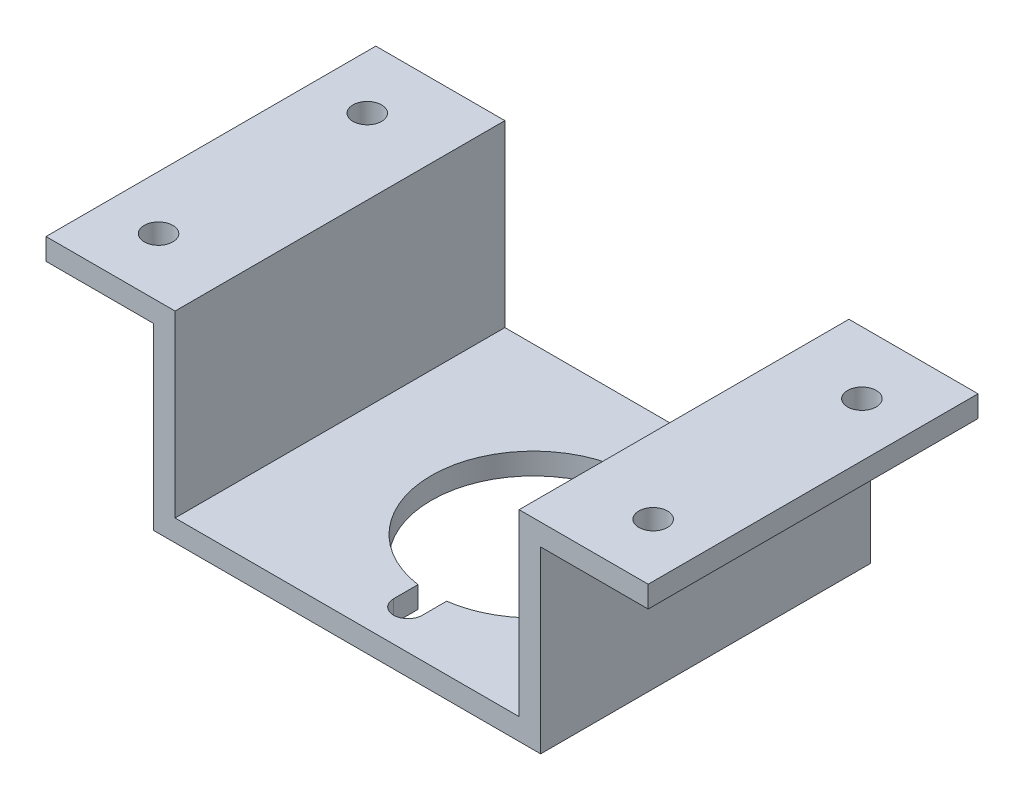
SolidWorks part; units mm, degrees
ref_plane "Front Plane" through (0, 0, 0) normal (0, 0, 1) x (1, 0, 0)
ref_plane "Top Plane" through (0, 0, 0) normal (0, 1, 0) x (1, 0, 0)
ref_plane "Right Plane" through (0, 0, 0) normal (1, 0, 0) x (0, 0, -1)
sketch "Sketch1" plane through (0, 0, 0) normal (0, 1, 0) x (1, 0, 0)
  line L1 (-23.0791, 14.3848) -> (26.9209, 14.3848)
  line L2 (-23.0791, 14.3848) -> (-23.0791, -25.6152)
  line L3 (-23.0791, -25.6152) -> (26.9209, -25.6152)
  line L4 (26.9209, 14.3848) -> (26.9209, -25.6152)
  dimension "D1" = 50
  dimension "D2" = 40
extrude "Boss-Extrude1" add sketch "Sketch1" along normal blind 3
sketch "Sketch2" plane through (0, 3, 0) normal (0, 1, 0) x (1, 0, 0)
  line L0 (-19.0791, 14.3848) -> (-19.0791, -25.6152)
  line L1 (26.9209, 14.3848) -> (-23.0791, 14.3848) construction
  line L2 (-23.0791, -25.6152) -> (26.9209, -25.6152) construction
  line L7 (-23.0791, 14.3848) -> (-23.0791, -25.6152)
  line L8 (-23.0791, -25.6152) -> (26.9209, -25.6152)
  line L9 (26.9209, -25.6152) -> (26.9209, 14.3848)
  line L10 (26.9209, 14.3848) -> (-23.0791, 14.3848)
  line L11 (-23.0791, 14.3848) -> (-23.0791, -25.6152)
  line L12 (-23.0791, -25.6152) -> (-19.0791, -25.6152)
  line L14 (-19.0791, 14.3848) -> (-23.0791, 14.3848)
  dimension "D1" = 0
  dimension "D2" = 4
sketch "Sketch5" plane through (0, 3, 0) normal (0, 1, 0) x (1, 0, 0)
  line L0 (24.9209, 14.3848) -> (24.9209, -25.6152)
  line L1 (26.9209, 14.3848) -> (-23.0791, 14.3848) construction
  line L2 (-23.0791, -25.6152) -> (26.9209, -25.6152) construction
  line L7 (-23.0791, 14.3848) -> (-23.0791, -25.6152)
  line L8 (-23.0791, -25.6152) -> (26.9209, -25.6152)
  line L9 (26.9209, -25.6152) -> (26.9209, 14.3848)
  line L10 (26.9209, 14.3848) -> (-23.0791, 14.3848)
  line L12 (24.9209, -25.6152) -> (26.9209, -25.6152)
  line L13 (26.9209, -25.6152) -> (26.9209, 14.3848)
  line L14 (26.9209, 14.3848) -> (24.9209, 14.3848)
  line L15 (-23.0791, 14.3848) -> (-23.0791, -25.6152)
  dimension "D1" = 0
  dimension "D2" = 2
sketch "Sketch6" plane through (0, 0, 0) normal (0, -1, 0) x (1, 0, 0)
  line L0 (-23.0791, 5.6152) -> (-1.0791, 5.6152)
  line L1 (-23.0791, -14.3848) -> (-23.0791, 25.6152) construction
  line L2 (6.9209, 5.6152) -> (6.9209, -11.8848)
  line L3 (-1.0791, 5.6152) -> (6.9209, 5.6152)
  line L4 (6.9209, 5.6152) -> (6.9209, 23.1152)
  line L5 (24.4209, 13.0152) -> (18.923, 13.0152)
  line L6 (6.9209, 5.6152) -> (24.4209, 5.6152)
  line L7 (24.4209, 5.6152) -> (24.4209, 13.0152)
  line L8 (24.4209, 5.6152) -> (24.4209, -1.7848)
  line L9 (24.4209, -1.7848) -> (18.923, -1.7848)
  arc A1 (18.923, 13.0152) -> (18.923, -1.7848) centre (6.9209, 5.6152) ccw
  circle A2 centre (6.9209, 23.1152) radius 2
  circle A3 centre (6.9209, -11.8848) radius 2
  dimension "D2" = 8
  dimension "D3" = 17.5
  dimension "D5" = 17.5
  dimension "D1" = 22
  dimension "D4" = 17.5
extrude "Cut-Extrude9" cut sketch "Sketch6" against normal blind 5
sketch "Sketch9" plane through (0, 0, 25.6152) normal (0, 0, 1) x (1, 0, 0)
sketch "Sketch16" plane through (24.4209, 0, 0) normal (-1, 0, 0) x (0, 0, 1)
  line L1 (13.0152, 0) -> (-1.7848, 0)
  line L2 (13.0152, 0) -> (13.0152, 3)
  line L3 (13.0152, 3) -> (-1.7848, 3)
  line L4 (-1.7848, 0) -> (-1.7848, 3)
extrude "Cut-Extrude10" cut sketch "Sketch16" against normal blind 0.5
sketch "Sketch21" plane through (0, 0, 0) normal (0, -1, 0) x (-1, 0, 0)
  circle A0 centre (-6.9209, -5.6152) radius 14.25
extrude "Cut-Extrude15" cut sketch "Sketch21" against normal blind 4
sketch "Sketch22" plane through (0, 3, 0) normal (0, 1, 0) x (1, 0, 0)
  line L0 (24.9209, 4.1848) -> (17.2661, 4.1848)
  line L1 (24.9209, -15.4152) -> (17.2661, -15.4152)
  line L2 (19.0989, 1.7848) -> (24.9209, 1.7848) construction
  line L3 (19.0989, -13.0152) -> (24.9209, -13.0152) construction
  circle A0 centre (6.9209, -5.6152) radius 15.9999
  arc A1 (19.0989, 1.7848) -> (19.0989, -13.0152) centre (6.9209, -5.6152) ccw construction
  arc M4 (19.0989, -13.0152) -> (19.0989, 1.7848) centre (6.9209, -5.6152) cw
  line M5 (19.0989, 1.7848) -> (24.9209, 1.7848)
  line M7 (24.9209, -13.0152) -> (19.0989, -13.0152)
  dimension "D1" = 2.4
  dimension "D2" = 2.4
extrude "Cut-Extrude16" cut sketch "Sketch22" against normal blind 4 contours A0 L0 M5 M4 | L1 A0 M7 M4
sketch "Sketch33" plane through (0, 3, 0) normal (0, 1, 0) x (1, 0, 0)
  line L0 (4.9209, 11.8848) -> (4.9209, -23.1152)
  line L1 (8.9209, -23.1152) -> (8.9209, 11.8848)
  line L2 (4.9209, 11.8848) -> (8.9209, 11.8848)
  line L3 (4.9209, -23.1152) -> (8.9209, -23.1152)
  circle A0 centre (6.9209, 11.8848) radius 2 construction
  circle A1 centre (6.9209, -23.1152) radius 2 construction
extrude "Cut-Extrude23" cut sketch "Sketch33" against normal blind 5
sketch "Sketch34" plane through (0, 0, -14.3848) normal (0, 0, -1) x (-1, 0, 0)
  line L0 (55, 0) -> (-55, 0) construction
  line L1 (-26.9209, 3) -> (23.066, 3)
  line L2 (-26.9209, 3) -> (-26.9209, 0)
  line L3 (-26.9209, 0) -> (23.066, 0)
  line L4 (23.066, 3) -> (23.066, 0)
extrude "Boss-Extrude2" add sketch "Sketch34" along normal blind 3
sketch "Sketch35" plane through (0, 0, 25.6152) normal (0, 0, 1) x (1, 0, 0)
  line L0 (55, 0) -> (-55, 0) construction
  line L1 (-23.0791, 3) -> (26.9209, 3)
  line L2 (-23.0791, 3) -> (-23.0791, 0)
  line L3 (-23.0791, 0) -> (26.9209, 0)
  line L4 (26.9209, 3) -> (26.9209, 0)
  line L5 (26.9209, 3) -> (26.9209, 0) construction
extrude "Boss-Extrude3" add sketch "Sketch35" along normal blind 3
sketch "Sketch36" plane through (26.9209, 0, 0) normal (1, 0, 0) x (0, 0, -1)
  line L0 (55, 0) -> (-55, 0) construction
  line L1 (-28.6152, 3) -> (17.3848, 3)
  line L2 (-28.6152, 3) -> (-28.6152, 0)
  line L3 (-28.6152, 0) -> (17.3848, 0)
  line L4 (17.3848, 3) -> (17.3848, 0)
  line L5 (17.3848, 3) -> (17.3848, 0) construction
extrude "Boss-Extrude4" add sketch "Sketch36" along normal blind 4
sketch "Sketch38" plane through (0, 3, 0) normal (0, 1, 0) x (1, 0, 0)
  line L0 (30.9209, -28.6152) -> (-23.0791, -28.6152) construction
  line L1 (30.9209, 17.3848) -> (27.9209, 17.3848)
  line L2 (30.9209, 17.3848) -> (30.9209, -28.6152)
  line L3 (30.9209, -28.6152) -> (27.9209, -28.6152)
  line L4 (27.9209, 17.3848) -> (27.9209, -28.6152)
  line L6 (-23.066, 17.3848) -> (-20.066, 17.3848)
  line L7 (-23.066, 17.3848) -> (-23.066, -28.6152)
  line L8 (-23.066, -28.6152) -> (-20.066, -28.6152)
  line L9 (-20.066, 17.3848) -> (-20.066, -28.6152)
  dimension "D1" = 3
  dimension "D2" = 3
extrude "Boss-Extrude5" add sketch "Sketch38" along normal blind 25
sketch "Sketch39" plane through (-23.066, 0, 0) normal (-1, 0, 0) x (0, 0, 1)
  line L1 (-17.3848, 28) -> (28.1507, 28)
  line L2 (-17.3848, 28) -> (-17.3848, 25)
  line L3 (-17.3848, 25) -> (28.1507, 25)
  line L4 (28.1507, 28) -> (28.1507, 25)
  dimension "D1" = 3
extrude "Boss-Extrude6" add sketch "Sketch39" along normal blind 15
sketch "Sketch40" plane through (30.9209, 0, 0) normal (1, 0, 0) x (0, 0, -1)
  line L0 (17.3848, 0) -> (17.3848, 28) construction
  line L1 (-28.6152, 28) -> (17.3848, 28)
  line L2 (-28.6152, 28) -> (-28.6152, 25)
  line L3 (-28.6152, 25) -> (17.3848, 25)
  line L4 (17.3848, 28) -> (17.3848, 25)
  dimension "D1" = 3
extrude "Boss-Extrude7" add sketch "Sketch40" along normal blind 15
sketch "Sketch41" plane through (-23.066, 0, 0) normal (-1, 0, 0) x (0, 0, 1)
  line L1 (28.6152, 28) -> (28.1507, 28)
  line L2 (28.6152, 28) -> (28.6152, 25)
  line L3 (28.6152, 25) -> (28.1507, 25)
  line L4 (28.1507, 28) -> (28.1507, 25)
extrude "Boss-Extrude8" add sketch "Sketch41" along normal blind 15
sketch "Sketch42" plane through (0, 25, 0) normal (0, -1, 0) x (1, 0, 0)
  line L0 (38.4209, 28.6152) -> (38.4209, -17.3848) construction
  line L1 (45.9209, 28.6152) -> (30.9209, 28.6152) construction
  line L2 (45.9209, -17.3848) -> (30.9209, -17.3848) construction
  line L3 (45.9209, 5.6152) -> (30.9209, -17.3848) construction
  line L4 (45.9209, 28.6152) -> (45.9209, -17.3848) construction
  line L5 (30.9209, 28.6152) -> (45.9209, 5.6152) construction
  line L6 (45.9209, 28.6152) -> (30.9209, 12.2239) construction
  line L7 (30.9209, 28.6152) -> (30.9209, -17.3848) construction
  line L8 (45.9209, -17.3848) -> (30.9209, 0) construction
  line L9 (44.2539, 0) -> (-44.2539, 0) construction
  circle A0 centre (38.4209, 20.4195) radius 2
  circle A2 centre (38.4209, -8.6924) radius 2
  dimension "D1" = 4
  dimension "D2" = 4
extrude "Cut-Extrude24" cut sketch "Sketch42" against normal blind 15 contours A0 | A2
sketch "Sketch43" plane through (0, 25, 0) normal (0, -1, 0) x (1, 0, 0)
  line L0 (-30.566, 28.6152) -> (-30.566, -17.3848) construction
  line L1 (-38.066, 28.6152) -> (-23.066, 28.6152) construction
  line L2 (-38.066, -17.3848) -> (-23.066, -17.3848) construction
  line L3 (40.4209, 20.4195) -> (-49.3024, 20.4195) construction
  line L4 (40.4209, -8.6924) -> (-52.4667, -8.6924) construction
  circle A0 centre (38.4209, 20.4195) radius 2 construction
  circle A1 centre (38.4209, -8.6924) radius 2 construction
  circle A2 centre (-30.566, 20.4195) radius 2
  circle A3 centre (-30.566, -8.6924) radius 2
  dimension "D1" = 4
extrude "Cut-Extrude25" cut sketch "Sketch43" against normal blind 15
